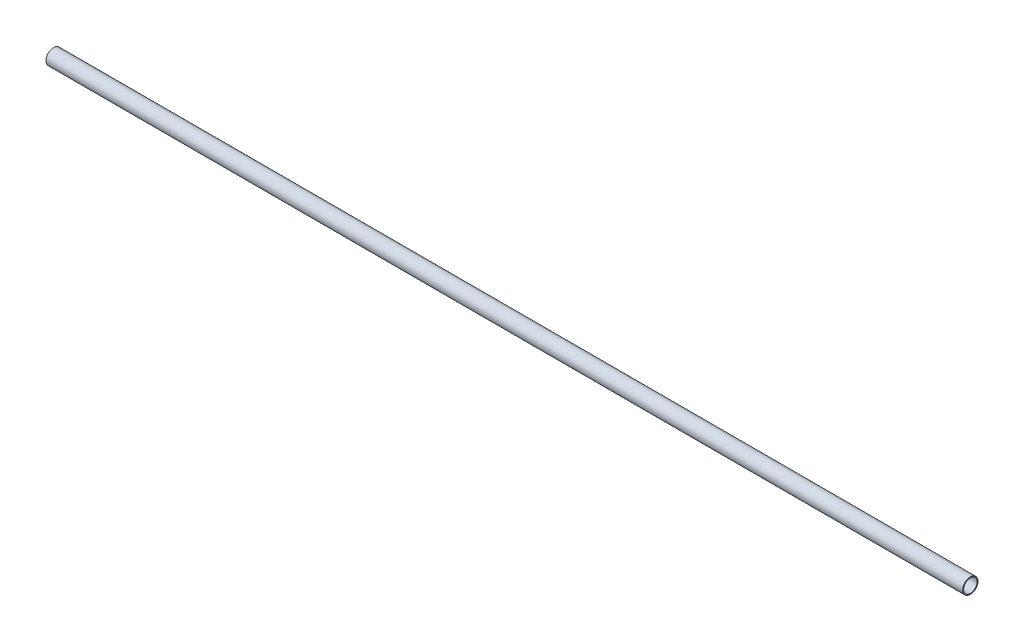
SolidWorks part; units mm, degrees
ref_plane "Front Plane" through (0, 0, 0) normal (0, 0, 1) x (1, 0, 0)
ref_plane "Top Plane" through (0, 0, 0) normal (0, 1, 0) x (1, 0, 0)
ref_plane "Right Plane" through (0, 0, 0) normal (1, 0, 0) x (0, 0, -1)
sketch "Sketch1" plane through (0, 0, 0) normal (1, 0, 0) x (0, 0, -1)
  circle A1 centre (0, 0) radius 11
  circle A2 centre (0, 0) radius 12.5
  dimension "D1" = 1.5
extrude "Boss-Extrude1" add sketch "Sketch1" along normal blind 1500
